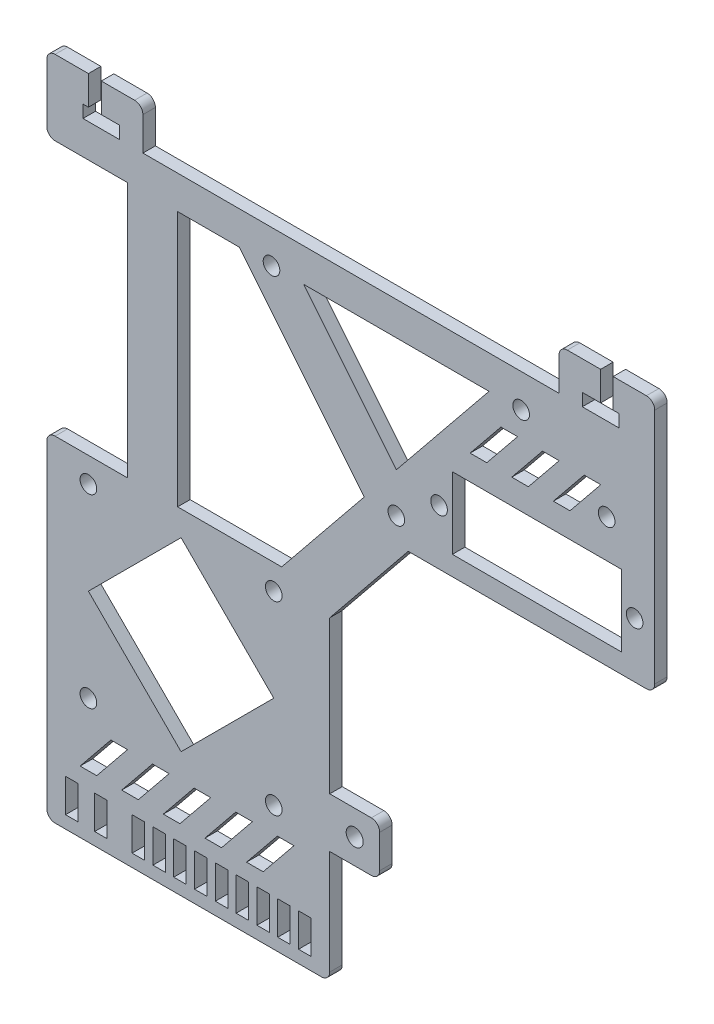
SolidWorks part; units mm, degrees
material "Zoltek Panex 33"
ref_plane "前视基准面" through (0, 0, 0) normal (0, 0, 1) x (1, 0, 0)
ref_plane "上视基准面" through (0, 0, 0) normal (0, 1, 0) x (1, 0, 0)
ref_plane "右视基准面" through (0, 0, 0) normal (1, 0, 0) x (0, 0, -1)
sketch "草图1" plane through (0, 0, 0) normal (0, 0, 1) x (1, 0, 0)
  line L0 (0, 0) -> (11.1369, 11.1369) construction
  line L1 (0, 0) -> (31, 0) construction
  line L10 (31, 0) -> (31, 30) construction
  line L11 (31, 30) -> (54.5, 30) construction
  line L12 (-11.1369, -11.1369) -> (-16.1369, -11.1369) construction
  line L13 (52.9, 25.7) -> (32.6, 25.7)
  line L14 (52.9, 25.7) -> (52.9, 34.3)
  line L15 (52.9, 34.3) -> (32.6, 34.3)
  line L16 (32.6, 25.7) -> (32.6, 34.3)
  line L17 (52.9, 25.7) -> (32.6, 34.3) construction
  line L18 (52.9, 34.3) -> (32.6, 25.7) construction
  line L19 (-16.1369, -11.1369) -> (-16.1369, -26.1369) construction
  line L20 (-16.1369, -26.1369) -> (-16.1369, 14.1369)
  line L21 (-16.1369, 53.8631) -> (-11.1369, 53.8631)
  line L25 (-9.5869, 53.8631) -> (-4.5869, 53.8631)
  line L26 (-4.5869, 53.8631) -> (-4.5869, 48.8631)
  line L27 (-4.5869, 48.8631) -> (45.4131, 48.8631)
  line L28 (45.4131, 48.8631) -> (45.4131, 53.8631)
  line L29 (45.4131, 53.8631) -> (50.4131, 53.8631)
  line L30 (50.4131, 53.8631) -> (50.4131, 50.3631)
  line L31 (50.4131, 48.8631) -> (51.9131, 48.8631)
  line L33 (51.9131, 53.8631) -> (56.9131, 53.8631)
  line L34 (56.9131, 53.8631) -> (56.9131, 23.3631)
  line L35 (56.9131, 23.3631) -> (27.2929, 23.3631)
  line L37 (17.8631, -26.1369) -> (-16.1369, -26.1369)
  line L38 (-11.1369, 53.8631) -> (-11.1369, 50.3631)
  line L39 (48.2131, 50.3631) -> (48.2131, 48.8631)
  line L40 (51.9131, 53.8631) -> (50.4131, 53.8631) construction
  line L41 (51.1631, 53.8631) -> (51.1631, 48.8631) construction
  line L43 (48.2131, 50.3631) -> (50.4131, 50.3631)
  line L44 (48.2131, 48.8631) -> (50.4131, 48.8631)
  line L45 (52.6131, 48.8631) -> (51.9131, 48.8631)
  line L46 (52.6131, 50.3631) -> (52.6131, 48.8631)
  line L47 (52.6131, 50.3631) -> (51.9131, 50.3631)
  line L48 (51.9131, 50.3631) -> (51.9131, 53.8631)
  line L49 (-11.7869, 50.3631) -> (-11.7869, 48.8631)
  line L50 (-11.7869, 50.3631) -> (-11.1369, 50.3631)
  line L53 (-7.3869, 50.3631) -> (-7.3869, 48.8631)
  line L54 (-7.3869, 50.3631) -> (-9.5869, 50.3631)
  line L55 (-9.5869, 50.3631) -> (-9.5869, 53.8631)
  line L56 (-9.5869, 53.8631) -> (-11.1369, 53.8631) construction
  line L57 (41.5572, 5.2579) -> (36.45, 0) construction
  line L58 (-11.7869, 48.8631) -> (-7.3869, 48.8631)
  line L59 (36.45, 0) -> (23.9084, -12.9115) construction
  line L60 (50.4131, 43.8631) -> (51.9131, 43.8631) construction
  line L61 (10.8631, 44.8631) -> (40.8631, 44.8631) construction
  line L62 (-10.3869, -24.6369) -> (-8.8869, -24.6369)
  line L63 (15.6131, -24.6369) -> (14.1131, -24.6369)
  line L64 (15.6131, -24.6369) -> (15.6131, -20.6369)
  line L65 (15.6131, -20.6369) -> (14.1131, -20.6369)
  line L66 (14.1131, -24.6369) -> (14.1131, -20.6369)
  line L67 (15.6131, -24.6369) -> (14.1131, -20.6369) construction
  line L68 (15.6131, -20.6369) -> (14.1131, -24.6369) construction
  line L69 (13.1131, -24.6369) -> (11.6131, -24.6369)
  line L70 (13.1131, -24.6369) -> (13.1131, -20.6369)
  line L71 (13.1131, -20.6369) -> (11.6131, -20.6369)
  line L72 (11.6131, -24.6369) -> (11.6131, -20.6369)
  line L73 (13.1131, -24.6369) -> (11.6131, -20.6369) construction
  line L74 (13.1131, -20.6369) -> (11.6131, -24.6369) construction
  line L75 (-13.8869, -24.6369) -> (-12.3869, -24.6369)
  line L76 (-13.8869, -24.6369) -> (-13.8869, -20.6369)
  line L77 (-13.8869, -20.6369) -> (-12.3869, -20.6369)
  line L78 (-12.3869, -24.6369) -> (-12.3869, -20.6369)
  line L79 (-13.8869, -24.6369) -> (-12.3869, -20.6369) construction
  line L80 (-13.8869, -20.6369) -> (-12.3869, -24.6369) construction
  line L81 (-10.3869, -24.6369) -> (-10.3869, -20.6369)
  line L82 (-8.8869, -24.6369) -> (-8.8869, -20.6369)
  line L83 (-10.3869, -24.6369) -> (-8.8869, -20.6369) construction
  line L84 (-10.3869, -20.6369) -> (-8.8869, -24.6369) construction
  line L85 (-10.3869, -20.6369) -> (-8.8869, -20.6369)
  line L89 (37.0009, 44.8631) -> (14.7253, 44.8631)
  line L90 (14.7253, 44.8631) -> (25.8631, 31.1265)
  line L95 (25.8631, 31.1265) -> (37.0009, 44.8631)
  line L98 (9.1131, -24.6369) -> (9.1131, -20.6369)
  line L99 (10.6131, -20.6369) -> (9.1131, -20.6369)
  line L100 (10.6131, -24.6369) -> (10.6131, -20.6369)
  line L101 (10.6131, -24.6369) -> (9.1131, -24.6369)
  line L102 (6.6131, -24.6369) -> (6.6131, -20.6369)
  line L103 (8.1131, -20.6369) -> (6.6131, -20.6369)
  line L104 (8.1131, -24.6369) -> (8.1131, -20.6369)
  line L105 (8.1131, -24.6369) -> (6.6131, -24.6369)
  line L106 (4.1131, -24.6369) -> (4.1131, -20.6369)
  line L107 (5.6131, -20.6369) -> (4.1131, -20.6369)
  line L108 (5.6131, -24.6369) -> (5.6131, -20.6369)
  line L109 (5.6131, -24.6369) -> (4.1131, -24.6369)
  line L110 (1.6131, -24.6369) -> (1.6131, -20.6369)
  line L111 (3.1131, -20.6369) -> (1.6131, -20.6369)
  line L112 (3.1131, -24.6369) -> (3.1131, -20.6369)
  line L113 (3.1131, -24.6369) -> (1.6131, -24.6369)
  line L114 (-0.8869, -24.6369) -> (-0.8869, -20.6369)
  line L115 (0.6131, -20.6369) -> (-0.8869, -20.6369)
  line L116 (0.6131, -24.6369) -> (0.6131, -20.6369)
  line L117 (0.6131, -24.6369) -> (-0.8869, -24.6369)
  line L118 (-3.3869, -24.6369) -> (-3.3869, -20.6369)
  line L119 (-1.8869, -20.6369) -> (-3.3869, -20.6369)
  line L120 (-1.8869, -24.6369) -> (-1.8869, -20.6369)
  line L121 (-1.8869, -24.6369) -> (-3.3869, -24.6369)
  line L122 (-5.8869, -24.6369) -> (-5.8869, -20.6369)
  line L123 (-4.3869, -20.6369) -> (-5.8869, -20.6369)
  line L124 (-4.3869, -24.6369) -> (-4.3869, -20.6369)
  line L125 (-4.3869, -24.6369) -> (-5.8869, -24.6369)
  line L128 (-6.4146, 44.8631) -> (-16.1369, 44.8631)
  line L129 (-11.1369, 0) -> (0, 11.1369)
  line L131 (-16.1369, 14.1369) -> (-6.4146, 14.1369)
  line L132 (-6.4146, 14.1369) -> (-6.4146, 44.8631)
  line L133 (-16.1369, 44.8631) -> (-16.1369, 53.8631)
  line L134 (22.0009, 26.3631) -> (12.0878, 14.1369)
  line L135 (12.0878, 14.1369) -> (-0.4146, 14.1369)
  line L136 (-0.4146, 14.1369) -> (-0.4146, 44.8631)
  line L137 (-11.1369, 0) -> (0, -11.1369)
  line L138 (0, 11.1369) -> (11.1369, 0)
  line L139 (0, -11.1369) -> (11.1369, 0)
  line L144 (23.8631, -12.5884) -> (17.8631, -12.5884)
  line L145 (17.8631, -12.5884) -> (17.8631, -26.1369)
  line L146 (23.8631, -6.5884) -> (17.8631, -6.5884)
  line L147 (17.8631, -6.5884) -> (17.8631, 11.733)
  line L149 (23.8631, -6.5884) -> (23.8631, -12.5884)
  line L150 (27.2929, 23.3631) -> (17.8631, 11.733)
  line L152 (22.0009, 26.3631) -> (7.0009, 44.8631)
  line L153 (7.0009, 44.8631) -> (-0.4146, 44.8631)
  line L154 (38.4306, 41.8631) -> (34.7309, 37.3)
  line L155 (38.4306, 41.8631) -> (40.4306, 41.8631)
  line L156 (34.7309, 37.3) -> (36.7309, 37.3)
  line L157 (40.4306, 41.8631) -> (36.7309, 37.3)
  line L158 (43.4306, 41.8631) -> (39.7309, 37.3)
  line L159 (43.4306, 41.8631) -> (45.4306, 41.8631)
  line L160 (45.4306, 41.8631) -> (41.7309, 37.3)
  line L161 (39.7309, 37.3) -> (41.7309, 37.3)
  line L162 (48.4306, 41.8631) -> (44.7309, 37.3)
  line L163 (48.4306, 41.8631) -> (50.4306, 41.8631)
  line L164 (50.4306, 41.8631) -> (46.7309, 37.3)
  line L165 (44.7309, 37.3) -> (46.7309, 37.3)
  line L166 (-8.4371, -14.1369) -> (-12.1369, -18.7)
  line L167 (-8.4371, -14.1369) -> (-6.4371, -14.1369)
  line L168 (-12.1369, -18.7) -> (-10.1369, -18.7)
  line L169 (-6.4371, -14.1369) -> (-10.1369, -18.7)
  line L170 (-3.4371, -14.1369) -> (-7.1369, -18.7)
  line L171 (-3.4371, -14.1369) -> (-1.4371, -14.1369)
  line L172 (-1.4371, -14.1369) -> (-5.1369, -18.7)
  line L173 (-7.1369, -18.7) -> (-5.1369, -18.7)
  line L174 (1.5629, -14.1369) -> (-2.1369, -18.7)
  line L175 (1.5629, -14.1369) -> (3.5629, -14.1369)
  line L176 (3.5629, -14.1369) -> (-0.1369, -18.7)
  line L177 (-2.1369, -18.7) -> (-0.1369, -18.7)
  line L178 (6.5629, -14.1369) -> (2.8631, -18.7)
  line L179 (6.5629, -14.1369) -> (8.5629, -14.1369)
  line L180 (8.5629, -14.1369) -> (4.8631, -18.7)
  line L181 (2.8631, -18.7) -> (4.8631, -18.7)
  line L182 (11.5629, -14.1369) -> (7.8631, -18.7)
  line L183 (11.5629, -14.1369) -> (13.5629, -14.1369)
  line L184 (13.5629, -14.1369) -> (9.8631, -18.7)
  line L185 (7.8631, -18.7) -> (9.8631, -18.7)
  line L186 (-11.1369, 0) -> (11.1369, 0) construction
  line L187 (0, 11.1369) -> (0, -11.1369) construction
  circle A0 centre (11.1369, 11.1369) radius 1
  circle A4 centre (31, 30) radius 1
  circle A5 centre (54.5, 30) radius 1
  circle A6 centre (20.8631, -9.5884) radius 1.025
  circle A7 centre (36.45, 0) radius 18.3 construction
  circle A8 centre (25.8631, 26.3631) radius 1
  circle A9 centre (40.8631, 44.8631) radius 1
  circle A10 centre (10.8631, 44.8631) radius 1
  circle A11 centre (51.1381, 38.8631) radius 1
  circle A13 centre (11.1369, -11.1369) radius 1
  circle A14 centre (-11.1369, -11.1369) radius 1
  circle A15 centre (-11.1369, 11.1369) radius 1
  point P19 (42.75, 30)
  point P63 (25.8631, 44.8631)
  point P68 (12.3631, -22.6369)
  point P77 (14.8631, -22.6369)
  point P78 (-9.6369, -22.6369)
  point P84 (-13.1369, -22.6369)
  point P95 (5.5685, 5.5685)
  dimension "D2" = 2
  dimension "D4" = 2
  dimension "D5" = 2
  dimension "D28" = 2.05
  dimension "D31" = 2
  dimension "D32" = 2
  dimension "D33" = 2
  dimension "D36" = 2
  dimension "D53" = 4
  dimension "D1" = 15.75
  dimension "D6" = 20.3
  dimension "D7" = 8.6
  dimension "D8" = 23.5
  dimension "D9" = 30
  dimension "D10" = 31
  dimension "D11" = 5
  dimension "D12" = 2.2
  dimension "D13" = 1.5
  dimension "D14" = 50
  dimension "D15" = 5
  dimension "D16" = 5
  dimension "D17" = 5
  dimension "D18" = 5
  dimension "D19" = 5
  dimension "D20" = 6
  dimension "D21" = 2.2
  dimension "D22" = 1.5
  dimension "D23" = 2.2
  dimension "D24" = 2.2
  dimension "D25" = 1.5
  dimension "D26" = 1.55
  dimension "D27" = 3
  dimension "D29" = 3
  dimension "D30" = 42
  dimension "D34" = 18.5
  dimension "D35" = 30
  dimension "D37" = 5.775
  dimension "D38" = 5
  dimension "D39" = 30.5
  dimension "D40" = 65
  dimension "D41" = 1.5
  dimension "D42" = 1.5
  dimension "D43" = 18
  dimension "D44" = 3.5
  dimension "D45" = 4
  dimension "D46" = 2.5
  dimension "D47" = 6
  dimension "D48" = 4
  dimension "D49" = 1.5
  dimension "D50" = 2
  dimension "D51" = 3
  dimension "D52" = 3.5
  dimension "D54" = 15.75
  dimension "D55" = 80
  dimension "D57" = 3
  dimension "D58" = 3
  dimension "D59" = 6
  dimension "D60" = 3
  dimension "D61" = 3
  dimension "D62" = 34
  dimension "D63" = 3
  dimension "D64" = 3
  dimension "D65" = 2
  dimension "D66" = 3
  dimension "D67" = 3
  dimension "D68" = 3
  dimension "D70" = 3
  dimension "D71" = 4
  dimension "D72" = 2
  dimension "D74" = 50.964
  dimension "D75" = 50.964
  dimension "D76" = 3
  dimension "D77" = 3
  dimension "D78" = 1
  dimension "D79" = 50.964
  dimension "D56" = 8
  dimension "D69" = 3
  dimension "D73" = 5
extrude "凸台-拉伸1" add sketch "草图1" along normal blind 1.5
fillet "圆角1" radius 1 11 edges at (-16.1369, 44.8631, 0.75) (45.4131, 53.8631, 0.75) (56.9131, 53.8631, 0.75) (56.9131, 23.3631, 0.75) (23.8631, -6.5884, 0.75) (23.8631, -12.5884, 0.75) (17.8631, -26.1369, 0.75) (-16.1369, -26.1369, 0.75) (-4.5869, 53.8631, 0.75) (-16.1369, 14.1369, 0.75) (-16.1369, 53.8631, 0.75)
